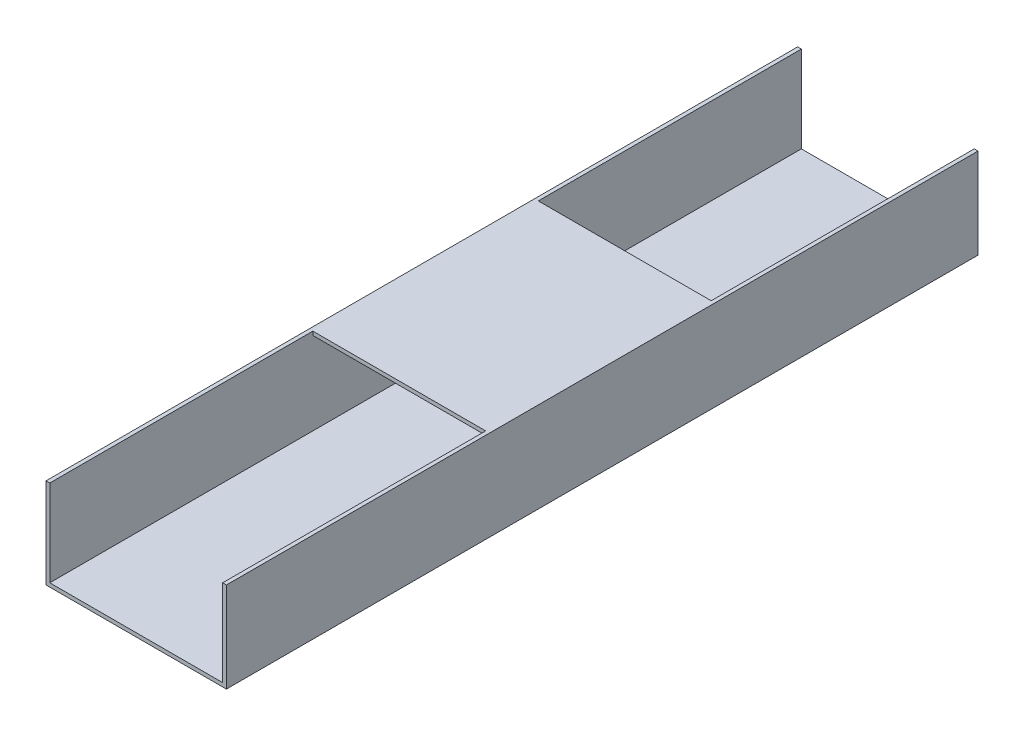
SolidWorks part; units mm, degrees
ref_plane "Front Plane" through (0, 0, 0) normal (0, 0, 1) x (1, 0, 0)
ref_plane "Top Plane" through (0, 0, 0) normal (0, 1, 0) x (1, 0, 0)
ref_plane "Right Plane" through (0, 0, 0) normal (1, 0, 0) x (0, 0, -1)
sketch "Sketch1" plane through (0, 0, 0) normal (0, 0, 1) x (1, 0, 0)
  line L0 (-23, 11) -> (23, 11)
  line L1 (-24, -12) -> (24, -12)
  line L2 (-24, -12) -> (-24, 12)
  line L3 (-24, 12) -> (24, 12)
  line L4 (24, -12) -> (24, 12)
  line L5 (-24, -12) -> (24, 12) construction
  line L6 (-24, 12) -> (24, -12) construction
  line L7 (23, -11) -> (23, 11)
  line L8 (-23, -11) -> (23, -11)
  line L9 (-23, -11) -> (-23, 11)
  point P0 (0, 0)
  dimension "D1" = 48
  dimension "D2" = 24
  dimension "D3" = 1
extrude "Boss-Extrude1" add sketch "Sketch1" along normal blind 200
sketch "Sketch2" plane through (0, 12, 0) normal (0, 1, 0) x (1, 0, 0)
  line L0 (-24, -100) -> (24, -100) construction
  line L1 (-24, -200) -> (-24, 0) construction
  line L2 (24, -200) -> (24, 0) construction
  line L3 (-23, -200) -> (23, -200)
  line L4 (-23, -70) -> (23, -70)
  line L5 (-23, -70) -> (-23, 0)
  line L6 (-23, 0) -> (23, 0)
  line L7 (23, -70) -> (23, 0)
  line L8 (-23, -70) -> (23, 0) construction
  line L9 (-23, 0) -> (23, -70) construction
  line L10 (23, -130) -> (23, -200)
  line L11 (-23, -130) -> (23, -130)
  line L12 (-23, -130) -> (-23, -200)
  point P6 (0, -35)
  point P20 (0, 0)
  dimension "D1" = 70
extrude "Cut-Extrude1" cut sketch "Sketch2" against normal blind 23
